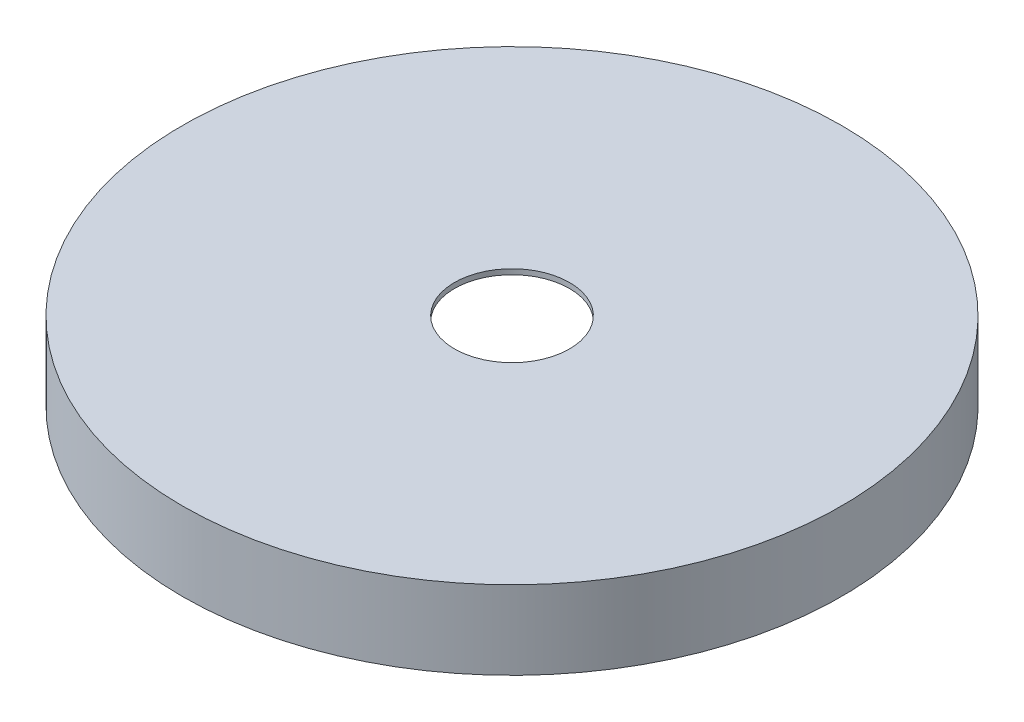
SolidWorks part; units mm, degrees
ref_plane "Front Plane" through (0, 0, 0) normal (0, 0, 1) x (1, 0, 0)
ref_plane "Top Plane" through (0, 0, 0) normal (0, 1, 0) x (1, 0, 0)
ref_plane "Right Plane" through (0, 0, 0) normal (1, 0, 0) x (0, 0, -1)
sketch "Sketch1" plane through (0, 0, 0) normal (0, 0, 1) x (1, 0, 0)
  line L0 (-160.02, 0) -> (-160.02, 38.1)
  line L2 (55, 0) -> (-55, 0) construction
  line L3 (-27.94, 35.56) -> (-157.48, 35.56)
  line L4 (-157.48, 0) -> (-157.48, 35.56)
  line L5 (0, -55) -> (0, 55) construction
  line L7 (-160.02, 38.1) -> (-27.94, 38.1)
  line L8 (-27.94, 38.1) -> (-27.94, 35.56)
  line L9 (-157.48, 0) -> (-160.02, 0)
  point P0 (0, 0)
  dimension "D1" = 160.02
  dimension "D2" = 38.1
  dimension "D3" = 2.54
  dimension "D4" = 2.54
  dimension "D5" = 27.94
ref_axis "Axis1" through (0, -2.54, 0) along (0, 1, 0)
revolve "Revolve1" add sketch "Sketch1" angle 360 about axis through (0, -2.54, 0) along (0, 1, 0)
